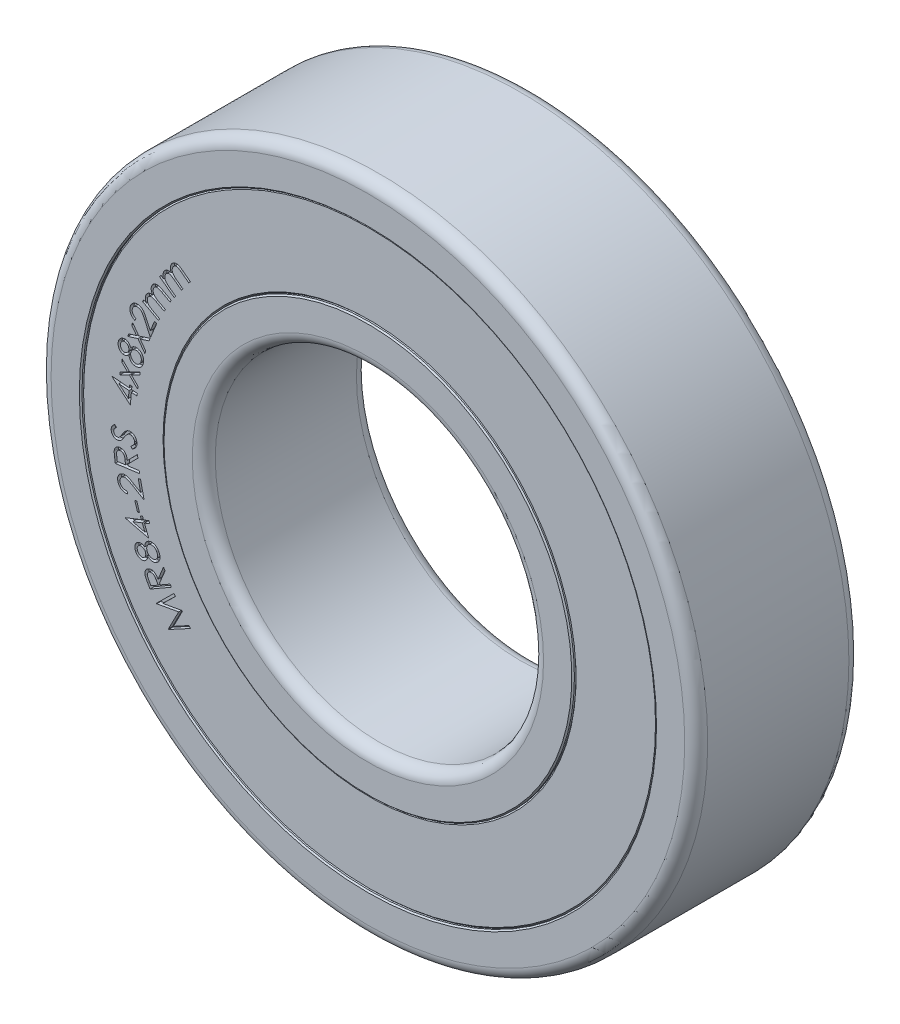
SolidWorks part; units mm, degrees
material "AISI 316 Annealed Stainless Steel Bar (SS)"
ref_plane "Front" through (0, 0, 0) normal (0, 0, 1) x (1, 0, 0)
ref_plane "Top" through (0, 0, 0) normal (0, 1, 0) x (1, 0, 0)
ref_plane "Right" through (0, 0, 0) normal (1, 0, 0) x (0, 0, -1)
sketch "LAYOUT R" plane through (0, 0, 0) normal (1, 0, 0) x (0, 0, -1)
  line L0 (-1, 2) -> (1, 2)
  line L1 (1, -4) -> (-1, -4) construction
  line L2 (1, -4) -> (1, 4) construction
  line L3 (1, 4) -> (-1, 4)
  line L4 (-1, -4) -> (-1, 4) construction
  line L5 (1, -4) -> (-1, 4) construction
  line L6 (1, 4) -> (-1, -4) construction
  line L7 (-1, 2.5) -> (1, 2.5)
  line L8 (-1, 3.5) -> (1, 3.5)
  line L11 (-17.5, 0) -> (17.5, 0) construction
  line L12 (-1, 4) -> (-1, 3.5)
  line L13 (1, 4) -> (1, 3.5)
  line L14 (-1, 3.5) -> (-1, 2.5)
  line L15 (1, 3.5) -> (1, 2.5)
  line L16 (-1, 2.5) -> (-1, 2)
  line L17 (1, 2.5) -> (1, 2)
  line L18 (-0.98, 3.5) -> (-0.98, 2.5)
  line L19 (0.98, 3.5) -> (0.98, 2.5)
  point P0 (0, 0)
  point P15 (0, 0)
  dimension "D1" = 2
  dimension "D2" = 8
  dimension "D3" = 2
  dimension "D6" = 0.02
  dimension "D7" = 0.02
  dimension "D4" = 2.5
  dimension "D5" = 3.5
sketch "Sketch R, INNER BODY" plane through (0, 0, 0) normal (1, 0, 0) x (0, 0, -1)
  line L0 (-1, 2) -> (1, 2) construction
  line L2 (-1, 2.5) -> (1, 2.5) construction
  line L4 (-1, 2) -> (1, 2)
  line L6 (-1, 2.5) -> (1, 2.5)
  line L8 (1, 2.5) -> (1, 2) construction
  line L9 (-1, 2.5) -> (-1, 2) construction
  line L10 (1, 2.5) -> (1, 2)
  line L11 (-1, 2.5) -> (-1, 2)
  line L12 (-17.5, 0) -> (17.5, 0) construction
  line L13 (-17.5, 0) -> (17.5, 0) construction
sketch "Sketch R, OUTER BODY" plane through (0, 0, 0) normal (1, 0, 0) x (0, 0, -1)
  line L2 (-1, 3.5) -> (1, 3.5) construction
  line L3 (1, 4) -> (-1, 4) construction
  line L6 (-1, 3.5) -> (1, 3.5)
  line L7 (1, 4) -> (-1, 4)
  line L8 (-17.5, 0) -> (17.5, 0) construction
  line L9 (-17.5, 0) -> (17.5, 0) construction
  line L10 (1, 4) -> (1, 3.5) construction
  line L11 (-1, 4) -> (-1, 3.5) construction
  line L12 (1, 4) -> (1, 3.5)
  line L13 (-1, 4) -> (-1, 3.5)
sketch "Sketch R, SEAL FACES" plane through (0, 0, 0) normal (1, 0, 0) x (0, 0, -1)
  line L0 (-17.5, 0) -> (17.5, 0) construction
  line L1 (-17.5, 0) -> (17.5, 0) construction
  line L3 (-1, 2.5) -> (1, 2.5) construction
  line L5 (-1, 3.5) -> (1, 3.5) construction
  line L7 (-0.98, 2.5) -> (0.98, 2.5)
  line L9 (-0.98, 3.5) -> (0.98, 3.5)
  line L10 (0.98, 3.5) -> (0.98, 2.5) construction
  line L11 (-0.98, 3.5) -> (-0.98, 2.5) construction
  line L12 (0.98, 3.5) -> (0.98, 2.5)
  line L13 (-0.98, 3.5) -> (-0.98, 2.5)
revolve "Revolve INNER BODY" add sketch "Sketch R, INNER BODY" angle 360 about L13
fillet "Fillet INNER BODY" radius 0.14 2 edges at (2, 0, 1) (2, 0, -1)
chamfer "Chamfer INNER BODY" distance 0.016 angle 45 2 edges at (2.5, 0, -1) (2.5, 0, 1)
revolve "Revolve OUTER BODY" add sketch "Sketch R, OUTER BODY" angle 360 about L9
fillet "Fillet OUTER BODY" radius 0.14 2 edges at (4, 0, -1) (4, 0, 1)
chamfer "Chamfer OUTER BODY" distance 0.016 angle 45 2 edges at (3.5, 0, 1) (3.5, 0, -1)
revolve "Revolve SEALS" add sketch "Sketch R, SEAL FACES" angle 360 about L1
chamfer "Chamfer SEALS" distance 0.016 angle 45 4 edges at (2.5, 0, -0.98) (3.5, 0, -0.98) (3.5, 0, 0.98) (2.5, 0, 0.98)
sketch "Sketch TEXT RADIUS 1 — MANUALLY ASSIGN TEXT AND FONT SIZE (FROM EQUATIONS)" plane through (0, 0, 0.98) normal (0, 0, 1) x (1, 0, 0)
  circle A0 centre (0, 0) radius 2.85 construction
  text T0 "MR84-2RS  4x8x2mm" font "Century Gothic" height 0.3
  dimension "D1" = 5.7
extrude "Cut-Extrude SEAL LABEL 1" cut sketch "Sketch TEXT RADIUS 1 — MANUALLY ASSIGN TEXT AND FONT SIZE (FROM EQUATIONS)" against normal blind 0.05
sketch "Sketch TEXT RADIUS 2 — MANUALLY ASSIGN TEXT AND FONT SIZE (FROM EQUATIONS)" plane through (0, 0, -0.98) normal (0, 0, -1) x (-1, 0, 0)
  circle A0 centre (0, 0) radius 2.85 construction
  text T0 "MR84-2RS  4x8x2mm" font "Century Gothic" height 0.3
  dimension "D1" = 5.7
extrude "Cut-Extrude SEAL LABEL 2" cut sketch "Sketch TEXT RADIUS 2 — MANUALLY ASSIGN TEXT AND FONT SIZE (FROM EQUATIONS)" against normal blind 0.05
equation "\"_i__BORE\"= 4"
equation "\"_i__OUTSIDE_DIAMETER\"= 8"
equation "\"_i__WIDTH\"= 2"
equation "\"_i_optional__TEXT_RADIUS_ADJUSTMENT\"= 0"
equation "\"_output__FONT_SIZE_mm\"= \"BODY_SPAN__SEAL__OF_RADIUS\" * \"param__FONT_SIZE_RATIO\"'MANUALLY ASSIGN TO FONT"
equation "\"BODY__HALF_WIDTH\"= \"_i__WIDTH\" / 2"
equation "\"BODY_SPAN___OF_DIAMETER\"= \"_i__OUTSIDE_DIAMETER\" - \"_i__BORE\""
equation "\"BODY_SPAN___OF_RADIUS\"= \"BODY_SPAN___OF_DIAMETER\" / 2"
equation "\"BODY_SPAN__BORE_AND_OD__OF RADIUS\"= ( \"BODY_SPAN___OF_RADIUS\" - \"BODY_SPAN__SEAL__OF_RADIUS\" ) / 2"
equation "\"BODY_SPAN__SEAL__OF_RADIUS\"= \"BODY_SPAN___OF_RADIUS\" * \"param__SEAL_PANEL_SPAN__RATIO_OF_BODY_RADIAN\""
equation "\"BORE__RADIUS\"= \"_i__BORE\" / 2"
equation "\"CORNER_RADII\"= \"_i__WIDTH\" * \"param__CORNER_RADII__ISO_MAX_RATIO_TO_WIDTH\""
equation "\"param__CORNER_RADII__ISO_MAX_RATIO_TO_WIDTH\"= 0.07'WHERE WIDTH IS LESS THAN DIAMETER"
equation "\"param__FONT_SIZE_RATIO\"= 0.3"
equation "\"param__SEAL_FACE_INSET__RATIO_OF_WIDTH\"= .01"
equation "\"param__SEAL_PANEL_SPAN__RATIO_OF_BODY_RADIAN\"= 0.5"
equation "\"param__SIDE_CHAMFERS__RATIO_TO_OD\"= 1 / 500"
equation "\"RING_INNER__OUTSIDE_RADIUS\"= \"BORE__RADIUS\" + \"BODY_SPAN__BORE_AND_OD__OF RADIUS\""
equation "\"RING_OUTER__OUTSIDE_RADIUS\"= ( \"_i__OUTSIDE_DIAMETER\" / 2 ) - \"BODY_SPAN__BORE_AND_OD__OF RADIUS\""
equation "\"SEAL_FACE_INSET\"= \"_i__WIDTH\" * \"param__SEAL_FACE_INSET__RATIO_OF_WIDTH\""
equation "\"SIDE_FACE_AND_SEAL_CHAMFERS\"= \"_i__OUTSIDE_DIAMETER\" * \"param__SIDE_CHAMFERS__RATIO_TO_OD\""
equation "\"TEXT_RADIUS\"= \"_i__BORE\" + ( \"BODY_SPAN___OF_DIAMETER\" / 2 ) - \"_output__FONT_SIZE_mm\" + \"_i_optional__TEXT_RADIUS_ADJUSTMENT\""
equation "\"D1@Chamfer INNER BODY\"=\"SIDE_FACE_AND_SEAL_CHAMFERS\""
equation "\"D1@Chamfer OUTER BODY\"=\"SIDE_FACE_AND_SEAL_CHAMFERS\""
equation "\"D1@Chamfer SEALS\"=\"SIDE_FACE_AND_SEAL_CHAMFERS\""
equation "\"D1@Fillet INNER BODY\"=\"CORNER_RADII\""
equation "\"D1@Fillet OUTER BODY\"=\"CORNER_RADII\""
equation "\"D1@LAYOUT R\"=\"_i__WIDTH\""
equation "\"D1@Sketch TEXT RADIUS 1 — MANUALLY ASSIGN TEXT AND FONT SIZE (FROM EQUATIONS)\" = \"TEXT_RADIUS\""
equation "\"D1@Sketch TEXT RADIUS 2 — MANUALLY ASSIGN TEXT AND FONT SIZE (FROM EQUATIONS)\" = \"TEXT_RADIUS\""
equation "\"D2@LAYOUT R\"=\"_i__OUTSIDE_DIAMETER\""
equation "\"D3@LAYOUT R\"=\"BORE__RADIUS\""
equation "\"D4@LAYOUT R\"=\"RING_INNER__OUTSIDE_RADIUS\""
equation "\"D5@LAYOUT R\"=\"RING_OUTER__OUTSIDE_RADIUS\""
